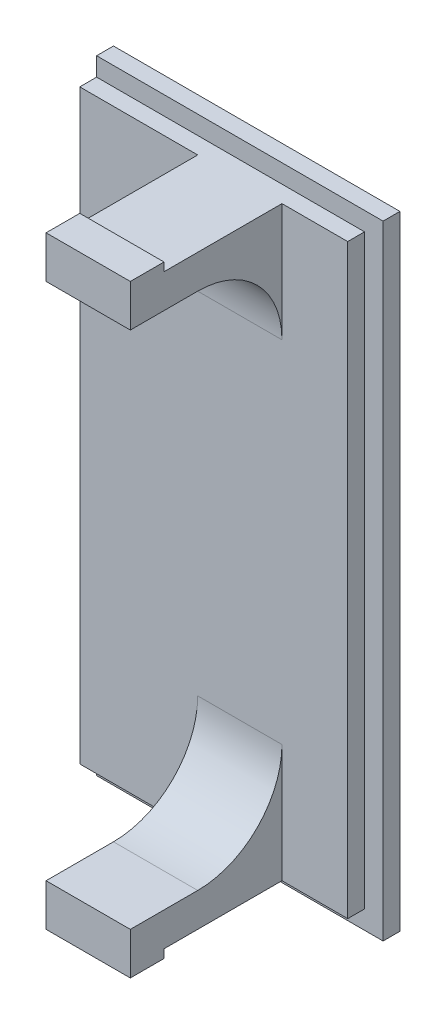
SolidWorks part; units mm, degrees
ref_plane "Plan de face" through (0, 0, 0) normal (0, 0, 1) x (1, 0, 0)
ref_plane "Plan de dessus" through (0, 0, 0) normal (0, 1, 0) x (1, 0, 0)
ref_plane "Plan de droite" through (0, 0, 0) normal (1, 0, 0) x (0, 0, -1)
sketch "Esquisse1" plane through (0, 0, 0) normal (0, 0, 1) x (1, 0, 0)
  line L1 (-17, 37) -> (17, 37)
  line L2 (-17, 37) -> (-17, -37)
  line L3 (-17, -37) -> (17, -37)
  line L4 (17, 37) -> (17, -37)
  point P4 (0, 37)
  point P6 (-17, 0)
  dimension "D1" = 34
  dimension "D2" = 74
extrude "Boss.-Extru.1" add sketch "Esquisse1" along normal blind 2
sketch "Esquisse2" plane through (0, 0, 2) normal (0, 0, 1) x (1, 0, 0)
  line L0 (-17, 37) -> (-17, -37) construction
  line L1 (-17, 34.8) -> (14.8, 34.8)
  line L2 (-17, 34.8) -> (-17, -34.8)
  line L3 (-17, -34.8) -> (14.8, -34.8)
  line L4 (14.8, 34.8) -> (14.8, -34.8)
  line L5 (17, 37) -> (-17, 37) construction
  line L6 (17, -37) -> (17, 37) construction
  line L7 (-17, -37) -> (17, -37) construction
  dimension "D1" = 2.2
  dimension "D2" = 2.2
  dimension "D3" = 2.2
extrude "Boss.-Extru.2" add sketch "Esquisse2" along normal blind 2
sketch "Esquisse7" plane through (0, 0, 4) normal (0, 0, 1) x (1, 0, 0)
  line L0 (14.8, 34.8) -> (-17, 34.8) construction
  line L1 (-3, 34.8) -> (7, 34.8)
  line L2 (-3, 34.8) -> (-3, 30.8)
  line L3 (-3, 30.8) -> (7, 30.8)
  line L4 (7, 34.8) -> (7, 30.8)
  line L5 (-17, -34.8) -> (14.8, -34.8) construction
  line L6 (-3, -34.8) -> (7, -34.8)
  line L7 (-3, -34.8) -> (-3, -30.8)
  line L8 (-3, -30.8) -> (7, -30.8)
  line L9 (7, -34.8) -> (7, -30.8)
  line L10 (17, -37) -> (17, 37) construction
  dimension "D1" = 4
  dimension "D2" = 10
  dimension "D3" = 10
extrude "Boss.-Extru.5" add sketch "Esquisse7" along normal blind 18
sketch "Esquisse8" plane through (0, 0, 22) normal (0, 0, 1) x (1, 0, 0)
  line L1 (7, 30.8) -> (7, 34.8) construction
  line L2 (-3, 34.8) -> (7, 34.8)
  line L3 (-3, 34.8) -> (-3, 35.8)
  line L4 (-3, 35.8) -> (7, 35.8)
  line L5 (7, -34.8) -> (7, -30.8) construction
  line L6 (-3, -34.8) -> (7, -34.8)
  line L7 (-3, -34.8) -> (-3, -35.8)
  line L8 (-3, -35.8) -> (7, -35.8)
  line L10 (7, -34.8) -> (7, -35.8)
  line L11 (7, 34.8) -> (7, 35.8)
  dimension "D1" = 1
extrude "Boss.-Extru.6" add sketch "Esquisse8" against normal blind 4
fillet "Congé2" radius 10 2 edges at (2, 30.8, 4) (2, -30.8, 4)
